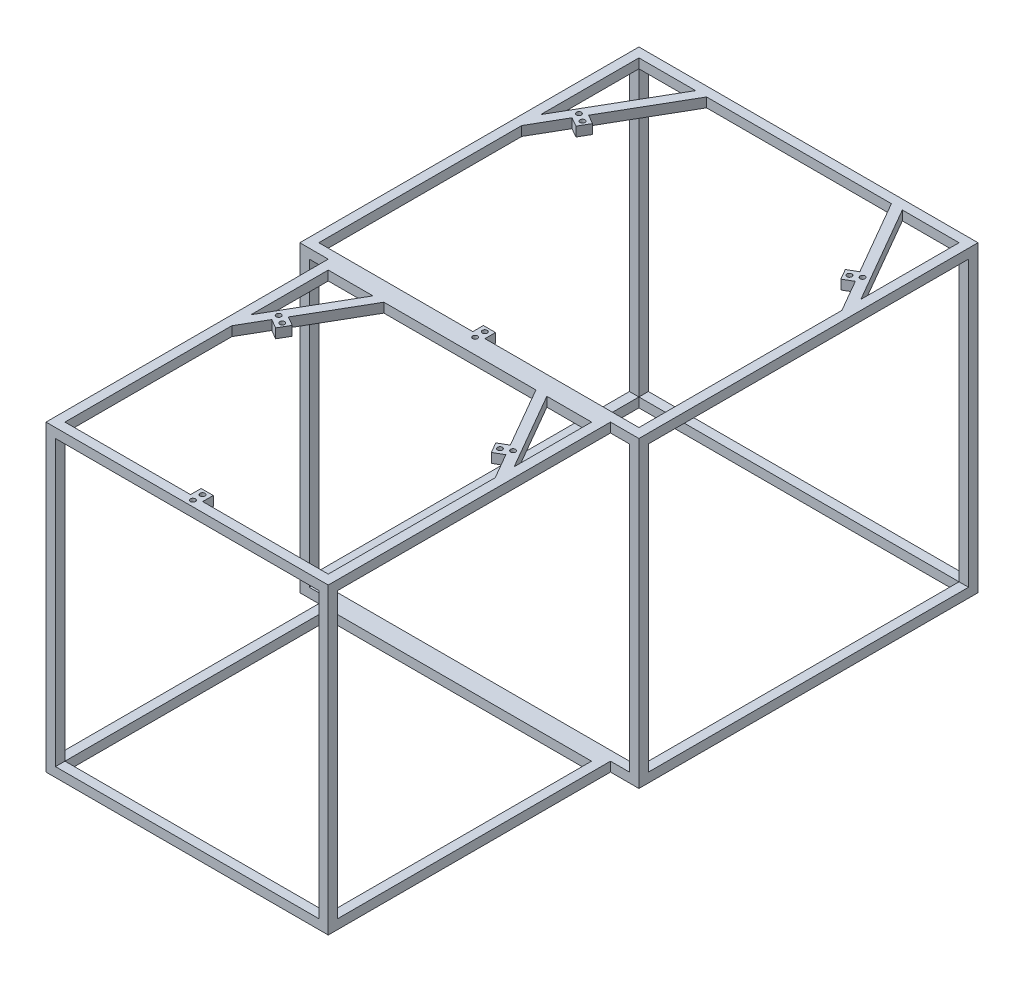
SolidWorks part; units mm, degrees
ref_plane "Front Plane" through (0, 0, 0) normal (0, 0, 1) x (1, 0, 0)
ref_plane "Top Plane" through (0, 0, 0) normal (0, 1, 0) x (1, 0, 0)
ref_plane "Right Plane" through (0, 0, 0) normal (1, 0, 0) x (0, 0, -1)
sketch "Sketch1" plane through (0, 0, 0) normal (0, 1, 0) x (1, 0, 0)
  line L0 (0, -447.45) -> (0, 894.9) construction
  line L1 (571.5768, -330) -> (0, 660) construction
  line L2 (0, 660) -> (-571.5768, -330) construction
  line L3 (-571.5768, -330) -> (571.5768, -330) construction
  line L4 (-387.5031, 223.725) -> (571.5768, -330) construction
  line L5 (387.5031, 223.725) -> (-775.0061, -447.45) construction
  line L6 (0, 634.9) -> (-549.8395, -317.45) construction
  line L7 (-549.8395, -317.45) -> (549.8395, -317.45) construction
  line L8 (549.8395, -317.45) -> (0, 634.9) construction
  line L9 (0, 894.9) -> (-775.0061, -447.45) construction
  line L10 (-775.0061, -447.45) -> (775.0061, -447.45) construction
  line L11 (775.0061, -447.45) -> (0, 894.9) construction
  line L12 (-395.5031, 209.8686) -> (16, -27.7128) construction
  line L13 (379.5031, 237.5814) -> (-32, 0) construction
  line L14 (16, -447.45) -> (16, 27.7128) construction
  line L15 (-379.5031, 237.5814) -> (32, 0) construction
  line L16 (395.5031, 209.8686) -> (-16, -27.7128) construction
  line L17 (-16, -447.45) -> (-16, 27.7128) construction
  line L18 (266.9198, 172.5814) -> (282.9927, 144.7423) construction
  line L19 (379.5031, 237.5814) -> (395.5031, 209.8686) construction
  line L20 (-379.5031, 237.5814) -> (-395.5031, 209.8686) construction
  line L21 (-282.9198, 144.8686) -> (-266.9198, 172.5814) construction
  line L22 (16, -447.45) -> (-16, -447.45) construction
  line L23 (16, -317.45) -> (-16, -317.45) construction
  line L24 (-266.9198, 172.5814) -> (-282.9198, 144.8686) construction
  line L25 (16, -447.45) -> (16, 1003.7978) construction
  line L26 (0, -447.45) -> (0, 1003.7978) construction
  line L27 (-16, -447.45) -> (-16, 1003.7978) construction
  line L28 (-379.5031, 237.5814) -> (741.6477, -409.7153) construction
  line L29 (-387.5031, 223.725) -> (733.6477, -423.5717) construction
  line L30 (-395.5031, 209.8686) -> (725.6477, -437.4281) construction
  line L31 (266.9198, 172.5814) -> (379.5031, 237.5814) construction
  line L32 (395.5031, 209.8686) -> (282.9927, 144.7423) construction
  line L33 (-379.5031, 237.5814) -> (-266.9198, 172.5814) construction
  line L34 (-282.9198, 144.8686) -> (-395.5031, 209.8686) construction
  line L35 (-16, -317.45) -> (16, -317.45) construction
  line L36 (16, -447.45) -> (-16, -447.45) construction
  line L37 (683.2074, -394.45) -> (0, 788.9) construction
  line L38 (0, 788.9) -> (-683.2074, -394.45) construction
  line L39 (-683.2074, -394.45) -> (683.2074, -394.45) construction
  line L40 (266.9198, 172.5814) -> (282.9927, 144.7423) construction
  line L41 (-266.9198, 172.5814) -> (-282.9198, 144.8686) construction
  line L42 (16, -317.45) -> (-16, -317.45) construction
  line L43 (379.5031, 237.5814) -> (-825.0348, -457.8589) construction
  line L44 (387.5031, 223.725) -> (-817.0348, -471.7153) construction
  line L45 (395.5031, 209.8686) -> (-809.0348, -485.5717) construction
  line L46 (333.6037, 211.0814) -> (349.6037, 183.3686) construction
  line L47 (-333.6037, 211.0814) -> (-349.6037, 183.3686) construction
  line L48 (16, -394.45) -> (-16, -394.45) construction
  line L49 (731.7049, -422.45) -> (0, 844.9) construction
  line L50 (0, 844.9) -> (-731.7049, -422.45) construction
  line L51 (-731.7049, -422.45) -> (-16, -422.45) construction
  line L52 (-571.5768, -447.45) -> (571.5768, -447.45) construction
  line L53 (330, -330) -> (330, 330) construction
  line L54 (330, 330) -> (-330, 330) construction
  line L55 (-330, 330) -> (-330, -330) construction
  line L56 (-330, -330) -> (330, -330) construction
  line L57 (447.45, -447.45) -> (447.45, 447.45) construction
  line L58 (447.45, 447.45) -> (-447.45, 447.45) construction
  line L59 (-447.45, 447.45) -> (-447.45, -447.45) construction
  line L60 (447.45, -330) -> (447.45, 447.45) construction
  line L61 (-447.45, 447.45) -> (-447.45, -330) construction
  line L62 (422.45, -447.45) -> (422.45, 422.45) construction
  line L63 (422.45, 422.45) -> (-422.45, 422.45) construction
  line L64 (-422.45, 422.45) -> (-422.45, -447.45) construction
  line L65 (-422.45, 422.45) -> (-272.7691, 422.45)
  line L66 (-272.7691, 422.45) -> (-422.45, 163.1951)
  line L67 (-422.45, 163.1951) -> (-422.45, 422.45)
  line L70 (-447.45, -447.45) -> (447.45, -447.45) construction
  line L73 (422.45, 113.1951) -> (422.45, -422.45)
  line L74 (422.45, -422.45) -> (16, -422.45)
  line L75 (-422.45, -422.45) -> (-422.45, 113.1951)
  line L78 (-349.6037, 183.3686) -> (-333.6037, 211.0814)
  line L79 (-333.6037, 211.0814) -> (-357.8524, 225.0814)
  line L80 (-357.8524, 225.0814) -> (-243.9016, 422.45)
  line L81 (-243.9016, 422.45) -> (243.9016, 422.45)
  line L85 (349.6037, 183.3686) -> (373.8524, 197.3686)
  line L86 (373.8524, 197.3686) -> (422.45, 113.1951)
  line L88 (272.7691, 422.45) -> (422.45, 163.1951)
  line L89 (422.45, 163.1951) -> (422.45, 422.45)
  line L90 (422.45, 422.45) -> (272.7691, 422.45)
  line L92 (-16, -422.45) -> (-422.45, -422.45)
  line L93 (16, -422.45) -> (731.7049, -422.45) construction
  line L94 (-731.7049, -422.45) -> (731.7049, -422.45) construction
  line L95 (-16, -422.45) -> (-16, -394.45)
  line L96 (-16, -394.45) -> (16, -394.45)
  line L97 (16, -394.45) -> (16, -422.45)
  line L98 (0, -447.45) -> (0, -1430.373) construction
  line L100 (347.45, -619.2996) -> (-519.9088, -1120.0695) construction
  line L101 (-441.673, -1074.9) -> (441.673, -1074.9) construction
  line L102 (441.673, -1074.9) -> (0, -309.9) construction
  line L103 (0, -309.9) -> (-441.673, -1074.9) construction
  line L104 (-347.45, -619.2996) -> (464.9155, -1088.3191) construction
  line L106 (645.1023, -1192.35) -> (0, -75) construction
  line L107 (0, -75) -> (-645.1023, -1192.35) construction
  line L108 (-645.1023, -1192.35) -> (645.1023, -1192.35) construction
  line L109 (0, -335) -> (-419.9357, -1062.35) construction
  line L110 (-419.9357, -1062.35) -> (419.9357, -1062.35) construction
  line L111 (419.9357, -1062.35) -> (0, -335) construction
  line L112 (0, -181) -> (-553.3036, -1139.35) construction
  line L113 (-553.3036, -1139.35) -> (553.3036, -1139.35) construction
  line L114 (553.3036, -1139.35) -> (0, -181) construction
  line L115 (372.45, -1192.35) -> (372.45, -447.45) construction
  line L116 (255, -1074.9) -> (255, -564.9) construction
  line L117 (255, -564.9) -> (-255, -564.9) construction
  line L118 (-255, -564.9) -> (-255, -1074.9) construction
  line L119 (-255, -1074.9) -> (255, -1074.9) construction
  line L120 (372.45, -447.45) -> (-372.45, -447.45) construction
  line L121 (-372.45, -447.45) -> (-372.45, -1192.35) construction
  line L122 (-441.673, -1192.35) -> (441.673, -1192.35) construction
  line L123 (-372.45, -447.45) -> (-372.45, -1074.9) construction
  line L124 (372.45, -1074.9) -> (372.45, -447.45) construction
  line L125 (-601.8011, -1167.35) -> (601.8011, -1167.35) construction
  line L126 (601.8011, -1167.35) -> (0, -125) construction
  line L127 (0, -125) -> (-601.8011, -1167.35) construction
  line L128 (347.45, -1192.35) -> (347.45, -472.45) construction
  line L129 (347.45, -472.45) -> (-347.45, -472.45) construction
  line L130 (-347.45, -472.45) -> (-347.45, -1192.35) construction
  line L131 (-372.45, -447.45) -> (372.45, -447.45) construction
  line L135 (-347.45, -472.45) -> (-229.4679, -472.45)
  line L136 (-229.4679, -472.45) -> (-347.45, -676.8011)
  line L137 (-347.45, -676.8011) -> (-347.45, -472.45)
  line L138 (229.4679, -472.45) -> (347.45, -472.45)
  line L139 (347.45, -472.45) -> (347.45, -676.8011)
  line L140 (347.45, -676.8011) -> (229.4679, -472.45)
  line L141 (-330.5512, -647.5314) -> (456.9155, -1102.1755) construction
  line L142 (314.5512, -619.8186) -> (-527.9088, -1106.2131) construction
  line L143 (-16, -447.45) -> (-16, -1430.373) construction
  line L144 (-314.5512, -619.8186) -> (472.9155, -1074.4627) construction
  line L145 (330.5512, -647.5314) -> (-511.9088, -1133.9259) construction
  line L146 (16, -447.45) -> (16, -1430.373) construction
  line L147 (-212.8365, -678.5436) -> (472.9155, -1074.4627) construction
  line L148 (-228.8365, -706.2564) -> (456.9155, -1102.1755) construction
  line L149 (228.8365, -706.2564) -> (-511.9088, -1133.9259) construction
  line L150 (212.8365, -678.5436) -> (-527.9088, -1106.2131) construction
  line L153 (-200.6004, -472.45) -> (200.6004, -472.45)
  line L154 (200.6004, -472.45) -> (292.9005, -632.3186)
  line L156 (268.6518, -646.3186) -> (284.6518, -674.0314)
  line L158 (308.9005, -660.0314) -> (347.45, -726.8011)
  line L159 (347.45, -726.8011) -> (347.45, -1167.35)
  line L160 (347.45, -1167.35) -> (16, -1167.35)
  line L161 (16, -1167.35) -> (16, -1139.35)
  line L162 (16, -1139.35) -> (-16, -1139.35)
  line L163 (-16, -1139.35) -> (-16, -1167.35)
  line L164 (-268.6518, -646.3186) -> (-284.6518, -674.0314)
  line L167 (-347.45, -726.8011) -> (-347.45, -1167.35)
  line L168 (-347.45, -1167.35) -> (-16, -1167.35) construction
  line L169 (-347.45, -1167.35) -> (-16, -1167.35)
  line L172 (333.6037, 211.0814) -> (357.8524, 225.0814)
  line L173 (357.8524, 225.0814) -> (243.9016, 422.45)
  line L175 (333.6037, 211.0814) -> (349.6037, 183.3686)
  line L177 (-447.45, -447.45) -> (-447.45, 447.45)
  line L178 (-447.45, 447.45) -> (447.45, 447.45)
  line L179 (447.45, 447.45) -> (447.45, -447.45)
  line L180 (447.45, -447.45) -> (372.45, -447.45)
  line L181 (372.45, -447.45) -> (372.45, -1192.35)
  line L182 (372.45, -1192.35) -> (-372.45, -1192.35)
  line L183 (-372.45, -1192.35) -> (-372.45, -447.45)
  line L184 (-372.45, -447.45) -> (-447.45, -447.45)
  line L185 (308.9005, -660.0314) -> (284.6518, -674.0314)
  line L186 (268.6518, -646.3186) -> (292.9005, -632.3186)
  line L191 (-422.45, 113.1951) -> (-373.8524, 197.3686)
  line L192 (-373.8524, 197.3686) -> (-349.6037, 183.3686)
  line L193 (-200.6004, -472.45) -> (-292.9005, -632.3186)
  line L194 (-292.9005, -632.3186) -> (-268.6518, -646.3186)
  line L197 (-347.45, -726.8011) -> (-308.9005, -660.0314)
  line L198 (-308.9005, -660.0314) -> (-284.6518, -674.0314)
  line L199 (220.8365, -692.4) -> (-519.9088, -1120.0695) construction
  line L200 (-220.8365, -692.4) -> (464.9155, -1088.3191) construction
  circle A0 centre (0, 0) radius 330 construction
  circle A1 centre (285.7884, 165) radius 6.75 construction
  circle A2 centre (-285.7884, 165) radius 6.75 construction
  circle A3 centre (0, -330) radius 6.75 construction
  circle A4 centre (0, 0) radius 330 construction
  circle A6 centre (0, -819.9) radius 255 construction
  circle A7 centre (-220.8365, -692.4) radius 6.75
  circle A8 centre (220.8365, -692.4) radius 6.75
  circle A9 centre (0, -1074.9) radius 6.75
  circle A10 centre (0, -819.9) radius 255 construction
  dimension "D1" = 660
  dimension "D4" = 13.5
  dimension "D5" = 13.5
  dimension "D6" = 13.5
  dimension "D13" = 660
  dimension "D16" = 510
  dimension "D19" = 13.5
  dimension "D20" = 13.5
  dimension "D21" = 13.5
  dimension "D22" = 117.45
  dimension "D25" = 510
  dimension "D2" = 120
  dimension "D3" = 120
  dimension "D11" = 53
  dimension "D17" = 120
  dimension "D18" = 120
  dimension "D27" = 25
  dimension "D28" = 25
  dimension "D29" = 16
  dimension "D7" = 12.55
  dimension "D8" = 130
  dimension "D9" = 16
  dimension "D10" = 16
  dimension "D12" = 25
  dimension "D14" = 117.45
  dimension "D15" = 25
  dimension "D23" = 12.55
  dimension "D24" = 53
  dimension "D26" = 117.45
  dimension "D30" = 16
extrude "Boss-Extrude1" add sketch "Sketch1" along normal blind 25 contours L184 L183 L182 L181 L180 L179 L178 L177 L90 L89 L88 L66 L67 L65 L136 L137 L135 L139 L140 L138 L191 L192 L78 L79 L80 L81 L173 L172 L175 L85 L86 L73 L74 L97 L96 L95 L92 L75 L197 L198 L164 L194 L193 L153 L154
sketch "Sketch2" plane through (0, 25, 0) normal (0, 1, 0) x (1, 0, 0)
  line L0 (0, -447.45) -> (0, -1430.373) construction
  line L1 (0, -447.45) -> (0, 894.9) construction
  line L2 (387.5031, 223.725) -> (-775.0061, -447.45) construction
  line L3 (-387.5031, 223.725) -> (571.5768, -330) construction
  line L4 (-347.45, -619.2996) -> (464.9155, -1088.3191) construction
  line L5 (347.45, -619.2996) -> (-519.9088, -1120.0695) construction
  line L6 (-272.7691, 422.45) -> (-422.45, 163.1951) construction
  line L7 (-229.4679, -472.45) -> (-347.45, -676.8011) construction
  line L8 (347.45, -676.8011) -> (229.4679, -472.45) construction
  line L9 (372.45, -1192.35) -> (-372.45, -1192.35) construction
  line L10 (272.7691, 422.45) -> (422.45, 163.1951) construction
  circle A1 centre (0, -432.2) radius 6.5
  circle A2 centre (374.2962, 216.1) radius 6.5
  circle A3 centre (352.2125, 203.35) radius 6.5
  circle A4 centre (-374.2962, 216.1) radius 6.5
  circle A5 centre (-352.2125, 203.35) radius 6.5
  circle A6 centre (0, -1177.1) radius 6.5
  circle A7 centre (0, -1151.6) radius 6.5
  circle A8 centre (-309.3443, -641.3) radius 6.5
  circle A9 centre (-287.2606, -654.05) radius 6.5
  circle A10 centre (309.3443, -641.3) radius 6.5
  circle A11 centre (287.2606, -654.05) radius 6.5
  circle A12 centre (0, -406.7) radius 6.5
  dimension "D1" = 13
  dimension "D2" = 13
  dimension "D3" = 13
  dimension "D4" = 13
  dimension "D5" = 13
  dimension "D6" = 13
  dimension "D7" = 13
  dimension "D8" = 13
  dimension "D9" = 13
  dimension "D10" = 13
  dimension "D11" = 13
  dimension "D12" = 13
  dimension "D13" = 15.25
  dimension "D14" = 25.5
  dimension "D15" = 25.5
  dimension "D16" = 25.5
  dimension "D17" = 25.5
  dimension "D18" = 25.5
  dimension "D19" = 25.5
  dimension "D21" = 15.25
  dimension "D22" = 15.25
  dimension "D23" = 15.25
  dimension "D24" = 15.25
  dimension "D20" = 15.25
extrude "Cut-Extrude1" cut sketch "Sketch2" against normal blind 25
sketch "Sketch3" plane through (0, 0, 0) normal (0, -1, 0) x (1, 0, 0)
  line L1 (-372.45, 1192.35) -> (-347.45, 1192.35)
  line L2 (-372.45, 1192.35) -> (-372.45, 1167.35)
  line L3 (-372.45, 1167.35) -> (-347.45, 1167.35)
  line L4 (-347.45, 1192.35) -> (-347.45, 1167.35)
  line L5 (372.45, 1192.35) -> (347.45, 1192.35)
  line L6 (372.45, 1192.35) -> (372.45, 1167.35)
  line L7 (372.45, 1167.35) -> (347.45, 1167.35)
  line L8 (347.45, 1192.35) -> (347.45, 1167.35)
  line L9 (447.45, 447.45) -> (422.45, 447.45)
  line L10 (447.45, 447.45) -> (447.45, 422.45)
  line L11 (447.45, 422.45) -> (422.45, 422.45)
  line L12 (422.45, 447.45) -> (422.45, 422.45)
  line L13 (-447.45, 447.45) -> (-422.45, 447.45)
  line L14 (-447.45, 447.45) -> (-447.45, 422.45)
  line L15 (-447.45, 422.45) -> (-422.45, 422.45)
  line L16 (-422.45, 447.45) -> (-422.45, 422.45)
  line L17 (422.45, -422.45) -> (447.45, -422.45)
  line L18 (422.45, -422.45) -> (422.45, -447.45)
  line L19 (422.45, -447.45) -> (447.45, -447.45)
  line L20 (447.45, -422.45) -> (447.45, -447.45)
  line L21 (-422.45, -422.45) -> (-447.45, -422.45)
  line L22 (-422.45, -422.45) -> (-422.45, -447.45)
  line L23 (-422.45, -447.45) -> (-447.45, -447.45)
  line L24 (-447.45, -422.45) -> (-447.45, -447.45)
extrude "Boss-Extrude2" add sketch "Sketch3" along normal blind 750
sketch "Sketch4" plane through (0, -750, 0) normal (0, -1, 0) x (1, 0, 0)
  line L0 (-372.45, 447.45) -> (-372.45, 1192.35)
  line L1 (-447.45, 447.45) -> (-372.45, 447.45)
  line L2 (-447.45, 447.45) -> (-447.45, -447.45)
  line L3 (-447.45, -447.45) -> (447.45, -447.45)
  line L4 (447.45, 447.45) -> (447.45, -447.45)
  line L5 (-422.45, 422.45) -> (422.45, 422.45)
  line L6 (-422.45, 422.45) -> (-422.45, -422.45)
  line L7 (-422.45, -422.45) -> (422.45, -422.45)
  line L8 (422.45, 422.45) -> (422.45, -422.45)
  line L9 (-372.45, 1192.35) -> (372.45, 1192.35)
  line L10 (372.45, 1192.35) -> (372.45, 447.45)
  line L11 (372.45, 447.45) -> (447.45, 447.45)
  line L12 (-347.45, 1167.35) -> (347.45, 1167.35)
  line L13 (-347.45, 1167.35) -> (-347.45, 472.45)
  line L14 (-347.45, 472.45) -> (347.45, 472.45)
  line L15 (347.45, 1167.35) -> (347.45, 472.45)
extrude "Boss-Extrude3" add sketch "Sketch4" along normal blind 25
